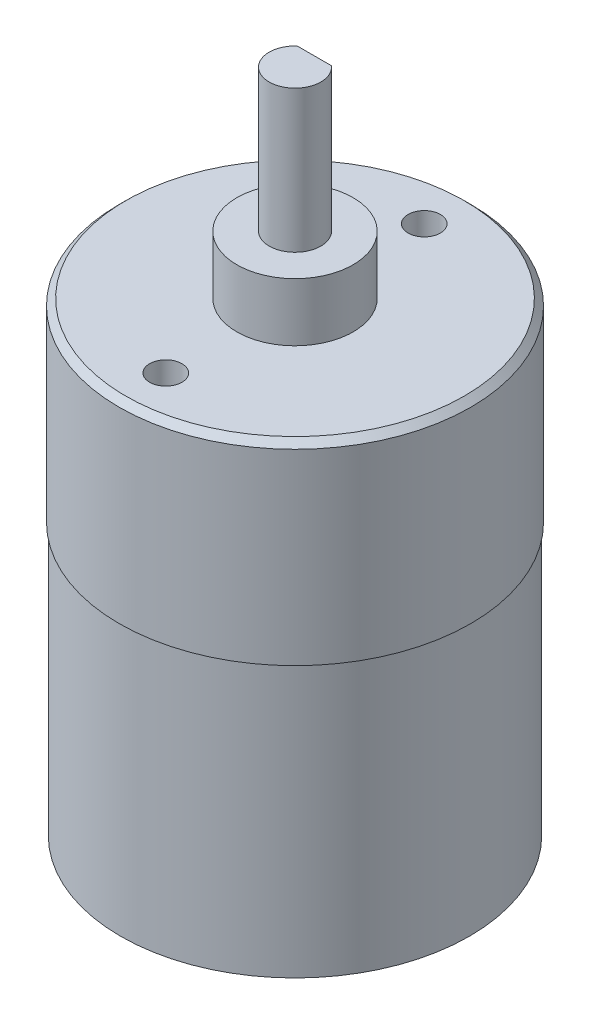
SolidWorks part; units mm, degrees
ref_plane "Plan de face" through (0, 0, 0) normal (0, 0, 1) x (1, 0, 0)
ref_plane "Plan de dessus" through (0, 0, 0) normal (0, 1, 0) x (1, 0, 0)
ref_plane "Plan de droite" through (0, 0, 0) normal (1, 0, 0) x (0, 0, -1)
sketch "Esquisse1" plane through (0, 0, 0) normal (0, 0, 1) x (1, 0, 0)
  line L0 (4.25, 1) -> (13.5, 1)
  line L1 (13.5, 1) -> (13.5, 22)
  line L2 (13.5, 22) -> (13.6, 22)
  line L3 (13.6, 22) -> (13.6, 37)
  line L4 (13.6, 37) -> (4.5, 37)
  line L5 (4.5, 37) -> (4.5, 41.5)
  line L6 (4.5, 41.5) -> (2, 41.5)
  line L7 (2, 41.5) -> (2, 52.5)
  line L8 (2, 52.5) -> (0, 52.5)
  line L9 (0, 52.5) -> (0, 0)
  line L10 (4.25, 1) -> (4.25, 0)
  line L11 (4.25, 0) -> (0, 0)
  point P4 (2.3982, 54.3076)
  dimension "D1" = 21
  dimension "D2" = 36
  dimension "D3" = 15.5
  dimension "D4" = 13.5
  dimension "D5" = 0.1
  dimension "D6" = 4.5
  dimension "D7" = 4.5
  dimension "D8" = 2
  dimension "D9" = 1
  dimension "D10" = 4.25
revolve "Révolution1" add sketch "Esquisse1" angle 360 about L9
sketch "Esquisse2" plane through (0, 52.5, 0) normal (0, 1, 0) x (1, 0, 0)
  line L0 (0, 0) -> (1.3229, 1.5) construction
  line L1 (0, 0) -> (0, 1.5) construction
  line L2 (-1.3229, 1.5) -> (1.3229, 1.5)
  line L3 (0, 2) -> (0, 1.5) construction
  line L4 (0, -2) -> (0, 0) construction
  circle A0 centre (0, 0) radius 2 construction
  arc A1 (1.3229, 1.5) -> (-1.3229, 1.5) centre (0, 0) ccw
  circle A2 centre (0, 0) radius 2 construction
  point P8 (0, -2)
  dimension "D1" = 3.5
extrude "Enlèv. mat.-Extru.1" cut sketch "Esquisse2" against normal blind 8.5
sketch "Esquisse3" plane through (0, 37, 0) normal (0, 1, 0) x (1, 0, 0)
  line L0 (0, 0) -> (0, 10) construction
  line L1 (0, 0) -> (5.046, 0) construction
  circle A0 centre (0, 10) radius 1.25
  circle A1 centre (0, -10) radius 1.25
  dimension "D1" = 2.5
  dimension "D2" = 10
extrude "Enlèv. mat.-Extru.2" cut sketch "Esquisse3" against normal blind 4
chamfer "Chanfrein1" distance 0.5 angle 45 1 edges at (-13.6, 37, 0)
